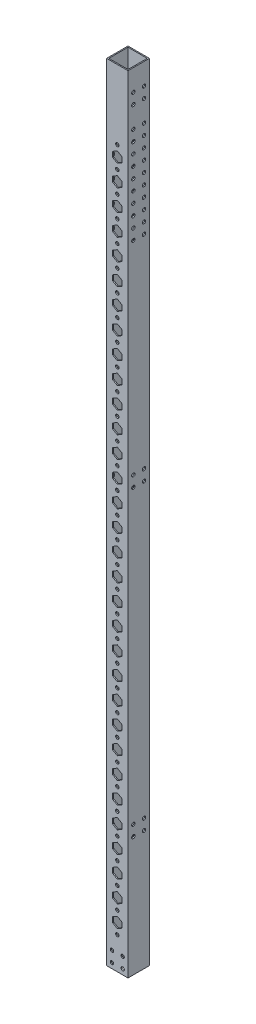
SolidWorks part; units mm, degrees
ref_plane "前视基准面" through (0, 0, 0) normal (0, 0, 1) x (1, 0, 0)
ref_plane "上视基准面" through (0, 0, 0) normal (0, 1, 0) x (1, 0, 0)
ref_plane "右视基准面" through (0, 0, 0) normal (1, 0, 0) x (0, 0, -1)
other "Configuration Table"
sketch "草图1" plane through (0, 0, 0) normal (0, 1, 0) x (1, 0, 0)
  line L1 (-10, -10) -> (10, -10)
  line L2 (-10, -10) -> (-10, 10)
  line L3 (-10, 10) -> (10, 10)
  line L4 (10, -10) -> (10, 10)
  line L5 (-10, -10) -> (10, 10) construction
  line L6 (-10, 10) -> (10, -10) construction
  point P0 (0, 0)
  dimension "D1" = 20
  dimension "D2" = 20
extrude "拉伸-薄壁1" add sketch "草图1" along normal blind 735 thin thin type one direction reverse wall 1
sketch "草图4" plane through (0, 0, 10) normal (0, 0, 1) x (1, 0, 0)
  line L0 (-10, 0) -> (10, 0) construction
  line L1 (0, 30) -> (0, 0) construction
  line L2 (10, 10) -> (-10, 10) construction
  line L3 (10, 735) -> (10, 0) construction
  line L4 (-10, 735) -> (-10, 0) construction
  line L5 (0, 30) -> (0, 50) construction
  line L6 (4.3301, 62.5) -> (0, 65)
  line L7 (0, 45) -> (-4.3301, 42.5)
  line L8 (-4.3301, 42.5) -> (-4.3301, 37.5)
  line L9 (-4.3301, 37.5) -> (0, 35)
  line L10 (0, 35) -> (4.3301, 37.5)
  line L11 (4.3301, 37.5) -> (4.3301, 42.5)
  line L12 (4.3301, 42.5) -> (0, 45)
  line L13 (4.3301, 57.5) -> (4.3301, 62.5)
  line L14 (0, 55) -> (4.3301, 57.5)
  line L15 (-4.3301, 57.5) -> (0, 55)
  line L16 (-4.3301, 62.5) -> (-4.3301, 57.5)
  line L17 (0, 65) -> (-4.3301, 62.5)
  line L18 (4.3301, 82.5) -> (0, 85)
  line L19 (4.3301, 77.5) -> (4.3301, 82.5)
  line L20 (0, 75) -> (4.3301, 77.5)
  line L21 (-4.3301, 77.5) -> (0, 75)
  line L22 (-4.3301, 82.5) -> (-4.3301, 77.5)
  line L23 (0, 85) -> (-4.3301, 82.5)
  line L24 (4.3301, 102.5) -> (0, 105)
  line L25 (4.3301, 97.5) -> (4.3301, 102.5)
  line L26 (0, 95) -> (4.3301, 97.5)
  line L27 (-4.3301, 97.5) -> (0, 95)
  line L28 (-4.3301, 102.5) -> (-4.3301, 97.5)
  line L29 (0, 105) -> (-4.3301, 102.5)
  line L30 (4.3301, 122.5) -> (0, 125)
  line L31 (4.3301, 117.5) -> (4.3301, 122.5)
  line L32 (0, 115) -> (4.3301, 117.5)
  line L33 (-4.3301, 117.5) -> (0, 115)
  line L34 (-4.3301, 122.5) -> (-4.3301, 117.5)
  line L35 (0, 125) -> (-4.3301, 122.5)
  line L36 (4.3301, 142.5) -> (0, 145)
  line L37 (4.3301, 137.5) -> (4.3301, 142.5)
  line L38 (0, 135) -> (4.3301, 137.5)
  line L39 (-4.3301, 137.5) -> (0, 135)
  line L40 (-4.3301, 142.5) -> (-4.3301, 137.5)
  line L41 (0, 145) -> (-4.3301, 142.5)
  line L42 (4.3301, 162.5) -> (0, 165)
  line L43 (4.3301, 157.5) -> (4.3301, 162.5)
  line L44 (0, 155) -> (4.3301, 157.5)
  line L45 (-4.3301, 157.5) -> (0, 155)
  line L46 (-4.3301, 162.5) -> (-4.3301, 157.5)
  line L47 (0, 165) -> (-4.3301, 162.5)
  line L48 (4.3301, 182.5) -> (0, 185)
  line L49 (4.3301, 177.5) -> (4.3301, 182.5)
  line L50 (0, 175) -> (4.3301, 177.5)
  line L51 (-4.3301, 177.5) -> (0, 175)
  line L52 (-4.3301, 182.5) -> (-4.3301, 177.5)
  line L53 (0, 185) -> (-4.3301, 182.5)
  line L54 (4.3301, 202.5) -> (0, 205)
  line L55 (4.3301, 197.5) -> (4.3301, 202.5)
  line L56 (0, 195) -> (4.3301, 197.5)
  line L57 (-4.3301, 197.5) -> (0, 195)
  line L58 (-4.3301, 202.5) -> (-4.3301, 197.5)
  line L59 (0, 205) -> (-4.3301, 202.5)
  line L60 (4.3301, 222.5) -> (0, 225)
  line L61 (4.3301, 217.5) -> (4.3301, 222.5)
  line L62 (0, 215) -> (4.3301, 217.5)
  line L63 (-4.3301, 217.5) -> (0, 215)
  line L64 (-4.3301, 222.5) -> (-4.3301, 217.5)
  line L65 (0, 225) -> (-4.3301, 222.5)
  line L66 (4.3301, 242.5) -> (0, 245)
  line L67 (4.3301, 237.5) -> (4.3301, 242.5)
  line L68 (0, 235) -> (4.3301, 237.5)
  line L69 (-4.3301, 237.5) -> (0, 235)
  line L70 (-4.3301, 242.5) -> (-4.3301, 237.5)
  line L71 (0, 245) -> (-4.3301, 242.5)
  line L72 (4.3301, 262.5) -> (0, 265)
  line L73 (4.3301, 257.5) -> (4.3301, 262.5)
  line L74 (0, 255) -> (4.3301, 257.5)
  line L75 (-4.3301, 257.5) -> (0, 255)
  line L76 (-4.3301, 262.5) -> (-4.3301, 257.5)
  line L77 (0, 265) -> (-4.3301, 262.5)
  line L78 (4.3301, 282.5) -> (0, 285)
  line L79 (4.3301, 277.5) -> (4.3301, 282.5)
  line L80 (0, 275) -> (4.3301, 277.5)
  line L81 (-4.3301, 277.5) -> (0, 275)
  line L82 (-4.3301, 282.5) -> (-4.3301, 277.5)
  line L83 (0, 285) -> (-4.3301, 282.5)
  line L84 (4.3301, 302.5) -> (0, 305)
  line L85 (4.3301, 297.5) -> (4.3301, 302.5)
  line L86 (0, 295) -> (4.3301, 297.5)
  line L87 (-4.3301, 297.5) -> (0, 295)
  line L88 (-4.3301, 302.5) -> (-4.3301, 297.5)
  line L89 (0, 305) -> (-4.3301, 302.5)
  line L90 (4.3301, 322.5) -> (0, 325)
  line L91 (4.3301, 317.5) -> (4.3301, 322.5)
  line L92 (0, 315) -> (4.3301, 317.5)
  line L93 (-4.3301, 317.5) -> (0, 315)
  line L94 (-4.3301, 322.5) -> (-4.3301, 317.5)
  line L95 (0, 325) -> (-4.3301, 322.5)
  line L96 (4.3301, 342.5) -> (0, 345)
  line L97 (4.3301, 337.5) -> (4.3301, 342.5)
  line L98 (0, 335) -> (4.3301, 337.5)
  line L99 (-4.3301, 337.5) -> (0, 335)
  line L100 (-4.3301, 342.5) -> (-4.3301, 337.5)
  line L101 (0, 345) -> (-4.3301, 342.5)
  line L102 (4.3301, 362.5) -> (0, 365)
  line L103 (4.3301, 357.5) -> (4.3301, 362.5)
  line L104 (0, 355) -> (4.3301, 357.5)
  line L105 (-4.3301, 357.5) -> (0, 355)
  line L106 (-4.3301, 362.5) -> (-4.3301, 357.5)
  line L107 (0, 365) -> (-4.3301, 362.5)
  line L108 (4.3301, 382.5) -> (0, 385)
  line L109 (4.3301, 377.5) -> (4.3301, 382.5)
  line L110 (0, 375) -> (4.3301, 377.5)
  line L111 (-4.3301, 377.5) -> (0, 375)
  line L112 (-4.3301, 382.5) -> (-4.3301, 377.5)
  line L113 (0, 385) -> (-4.3301, 382.5)
  line L114 (4.3301, 402.5) -> (0, 405)
  line L115 (4.3301, 397.5) -> (4.3301, 402.5)
  line L116 (0, 395) -> (4.3301, 397.5)
  line L117 (-4.3301, 397.5) -> (0, 395)
  line L118 (-4.3301, 402.5) -> (-4.3301, 397.5)
  line L119 (0, 405) -> (-4.3301, 402.5)
  line L120 (4.3301, 422.5) -> (0, 425)
  line L121 (4.3301, 417.5) -> (4.3301, 422.5)
  line L122 (0, 415) -> (4.3301, 417.5)
  line L123 (-4.3301, 417.5) -> (0, 415)
  line L124 (-4.3301, 422.5) -> (-4.3301, 417.5)
  line L125 (0, 425) -> (-4.3301, 422.5)
  line L126 (4.3301, 442.5) -> (0, 445)
  line L127 (4.3301, 437.5) -> (4.3301, 442.5)
  line L128 (0, 435) -> (4.3301, 437.5)
  line L129 (-4.3301, 437.5) -> (0, 435)
  line L130 (-4.3301, 442.5) -> (-4.3301, 437.5)
  line L131 (0, 445) -> (-4.3301, 442.5)
  line L132 (4.3301, 462.5) -> (0, 465)
  line L133 (4.3301, 457.5) -> (4.3301, 462.5)
  line L134 (0, 455) -> (4.3301, 457.5)
  line L135 (-4.3301, 457.5) -> (0, 455)
  line L136 (-4.3301, 462.5) -> (-4.3301, 457.5)
  line L137 (0, 465) -> (-4.3301, 462.5)
  line L138 (4.3301, 482.5) -> (0, 485)
  line L139 (4.3301, 477.5) -> (4.3301, 482.5)
  line L140 (0, 475) -> (4.3301, 477.5)
  line L141 (-4.3301, 477.5) -> (0, 475)
  line L142 (-4.3301, 482.5) -> (-4.3301, 477.5)
  line L143 (0, 485) -> (-4.3301, 482.5)
  line L144 (4.3301, 502.5) -> (0, 505)
  line L145 (4.3301, 497.5) -> (4.3301, 502.5)
  line L146 (0, 495) -> (4.3301, 497.5)
  line L147 (-4.3301, 497.5) -> (0, 495)
  line L148 (-4.3301, 502.5) -> (-4.3301, 497.5)
  line L149 (0, 505) -> (-4.3301, 502.5)
  line L150 (4.3301, 522.5) -> (0, 525)
  line L151 (4.3301, 517.5) -> (4.3301, 522.5)
  line L152 (0, 515) -> (4.3301, 517.5)
  line L153 (-4.3301, 517.5) -> (0, 515)
  line L154 (-4.3301, 522.5) -> (-4.3301, 517.5)
  line L155 (0, 525) -> (-4.3301, 522.5)
  line L156 (4.3301, 542.5) -> (0, 545)
  line L157 (4.3301, 537.5) -> (4.3301, 542.5)
  line L158 (0, 535) -> (4.3301, 537.5)
  line L159 (-4.3301, 537.5) -> (0, 535)
  line L160 (-4.3301, 542.5) -> (-4.3301, 537.5)
  line L161 (0, 545) -> (-4.3301, 542.5)
  line L162 (4.3301, 562.5) -> (0, 565)
  line L163 (4.3301, 557.5) -> (4.3301, 562.5)
  line L164 (0, 555) -> (4.3301, 557.5)
  line L165 (-4.3301, 557.5) -> (0, 555)
  line L166 (-4.3301, 562.5) -> (-4.3301, 557.5)
  line L167 (0, 565) -> (-4.3301, 562.5)
  line L168 (4.3301, 582.5) -> (0, 585)
  line L169 (4.3301, 577.5) -> (4.3301, 582.5)
  line L170 (0, 575) -> (4.3301, 577.5)
  line L171 (-4.3301, 577.5) -> (0, 575)
  line L172 (-4.3301, 582.5) -> (-4.3301, 577.5)
  line L173 (0, 585) -> (-4.3301, 582.5)
  line L174 (4.3301, 602.5) -> (0, 605)
  line L175 (4.3301, 597.5) -> (4.3301, 602.5)
  line L176 (0, 595) -> (4.3301, 597.5)
  line L177 (-4.3301, 597.5) -> (0, 595)
  line L178 (-4.3301, 602.5) -> (-4.3301, 597.5)
  line L179 (0, 605) -> (-4.3301, 602.5)
  line L180 (4.3301, 622.5) -> (0, 625)
  line L181 (4.3301, 617.5) -> (4.3301, 622.5)
  line L182 (0, 615) -> (4.3301, 617.5)
  line L183 (-4.3301, 617.5) -> (0, 615)
  line L184 (-4.3301, 622.5) -> (-4.3301, 617.5)
  line L185 (0, 625) -> (-4.3301, 622.5)
  line L186 (4.3301, 642.5) -> (0, 645)
  line L187 (4.3301, 637.5) -> (4.3301, 642.5)
  line L188 (0, 635) -> (4.3301, 637.5)
  line L189 (-4.3301, 637.5) -> (0, 635)
  line L190 (-4.3301, 642.5) -> (-4.3301, 637.5)
  line L191 (0, 645) -> (-4.3301, 642.5)
  line L192 (4.3301, 662.5) -> (0, 665)
  line L193 (4.3301, 657.5) -> (4.3301, 662.5)
  line L194 (0, 655) -> (4.3301, 657.5)
  line L195 (-4.3301, 657.5) -> (0, 655)
  line L196 (-4.3301, 662.5) -> (-4.3301, 657.5)
  line L197 (0, 665) -> (-4.3301, 662.5)
  circle A0 centre (0, 30) radius 1.6
  circle A1 centre (0, 50) radius 1.6
  circle A2 centre (0, 70) radius 1.6
  circle A3 centre (0, 90) radius 1.6
  circle A4 centre (0, 110) radius 1.6
  circle A5 centre (0, 130) radius 1.6
  circle A6 centre (0, 150) radius 1.6
  circle A7 centre (0, 170) radius 1.6
  circle A8 centre (0, 190) radius 1.6
  circle A9 centre (0, 210) radius 1.6
  circle A10 centre (0, 230) radius 1.6
  circle A11 centre (0, 250) radius 1.6
  circle A12 centre (0, 270) radius 1.6
  circle A13 centre (0, 290) radius 1.6
  circle A14 centre (0, 310) radius 1.6
  circle A15 centre (0, 330) radius 1.6
  circle A16 centre (0, 350) radius 1.6
  circle A17 centre (0, 370) radius 1.6
  circle A18 centre (0, 390) radius 1.6
  circle A19 centre (0, 410) radius 1.6
  circle A20 centre (0, 430) radius 1.6
  circle A21 centre (0, 450) radius 1.6
  circle A22 centre (0, 470) radius 1.6
  circle A23 centre (0, 490) radius 1.6
  circle A24 centre (0, 510) radius 1.6
  circle A25 centre (0, 530) radius 1.6
  circle A26 centre (0, 550) radius 1.6
  circle A27 centre (0, 570) radius 1.6
  circle A28 centre (0, 590) radius 1.6
  circle A29 centre (0, 610) radius 1.6
  circle A30 centre (0, 630) radius 1.6
  circle A31 centre (0, 650) radius 1.6
  circle A32 centre (0, 670) radius 1.6
  circle A33 centre (5, 5) radius 1.6
  circle A34 centre (-5, 5) radius 1.6
  circle A35 centre (-5, 15) radius 1.6
  circle A36 centre (5, 15) radius 1.6
  circle A37 centre (0, 40) radius 4.3301 construction
  circle A38 centre (0, 60) radius 4.3301 construction
  circle A39 centre (0, 80) radius 4.3301 construction
  circle A40 centre (0, 100) radius 4.3301 construction
  circle A41 centre (0, 120) radius 4.3301 construction
  circle A42 centre (0, 140) radius 4.3301 construction
  circle A43 centre (0, 160) radius 4.3301 construction
  circle A44 centre (0, 180) radius 4.3301 construction
  circle A45 centre (0, 200) radius 4.3301 construction
  circle A46 centre (0, 220) radius 4.3301 construction
  circle A47 centre (0, 240) radius 4.3301 construction
  circle A48 centre (0, 260) radius 4.3301 construction
  circle A49 centre (0, 280) radius 4.3301 construction
  circle A50 centre (0, 300) radius 4.3301 construction
  circle A51 centre (0, 320) radius 4.3301 construction
  circle A52 centre (0, 340) radius 4.3301 construction
  circle A53 centre (0, 360) radius 4.3301 construction
  circle A54 centre (0, 380) radius 4.3301 construction
  circle A55 centre (0, 400) radius 4.3301 construction
  circle A56 centre (0, 420) radius 4.3301 construction
  circle A57 centre (0, 440) radius 4.3301 construction
  circle A58 centre (0, 460) radius 4.3301 construction
  circle A59 centre (0, 480) radius 4.3301 construction
  circle A60 centre (0, 500) radius 4.3301 construction
  circle A61 centre (0, 520) radius 4.3301 construction
  circle A62 centre (0, 540) radius 4.3301 construction
  circle A63 centre (0, 560) radius 4.3301 construction
  circle A64 centre (0, 580) radius 4.3301 construction
  circle A65 centre (0, 600) radius 4.3301 construction
  circle A66 centre (0, 620) radius 4.3301 construction
  circle A67 centre (0, 640) radius 4.3301 construction
  circle A68 centre (0, 660) radius 4.3301 construction
  dimension "D1" = 3.2
  dimension "D6" = 3.2
  dimension "D2" = 30
  dimension "D4" = 20
  dimension "D5" = 10
  dimension "D7" = 5
  dimension "D8" = 5
  dimension "D9" = 5
  dimension "D10" = 15
  dimension "D3" = 33
extrude "切除-拉伸2" cut sketch "草图4" against normal through all
sketch "草图5" plane through (10, 0, 0) normal (1, 0, 0) x (0, 0, -1)
  line L0 (-10, 710) -> (10, 710) construction
  line L1 (-10, 735) -> (-10, 0) construction
  line L2 (10, 735) -> (10, 0) construction
  line L3 (-10, 735) -> (10, 735) construction
  line L4 (0, 735) -> (0, 710) construction
  line L5 (-10, 117) -> (10, 117) construction
  line L6 (-10, 0) -> (10, 0) construction
  line L7 (0, 117) -> (0, 0) construction
  line L8 (-10, 400) -> (10, 400) construction
  line L9 (0, 400) -> (0, 117) construction
  line L10 (-10, 640) -> (10, 640) construction
  circle A0 centre (-5, 715) radius 1.6
  circle A1 centre (5, 715) radius 1.6
  circle A2 centre (5, 705) radius 1.6
  circle A3 centre (-5, 705) radius 1.6
  circle A4 centre (-5, 112) radius 1.6
  circle A5 centre (5, 112) radius 1.6
  circle A6 centre (5, 122) radius 1.6
  circle A7 centre (-5, 122) radius 1.6
  circle A8 centre (-5, 395) radius 1.6
  circle A9 centre (5, 395) radius 1.6
  circle A10 centre (5, 405) radius 1.6
  circle A11 centre (-5, 405) radius 1.6
  circle A12 centre (-5, 645) radius 1.6
  circle A13 centre (5, 645) radius 1.6
  circle A14 centre (5, 635) radius 1.6
  circle A15 centre (-5, 635) radius 1.6
  circle A16 centre (-5, 625) radius 1.6
  circle A17 centre (5, 625) radius 1.6
  circle A18 centre (5, 615) radius 1.6
  circle A19 centre (-5, 615) radius 1.6
  circle A20 centre (-5, 605) radius 1.6
  circle A21 centre (5, 605) radius 1.6
  circle A22 centre (5, 595) radius 1.6
  circle A23 centre (-5, 595) radius 1.6
  circle A24 centre (-5, 685) radius 1.6
  circle A25 centre (5, 685) radius 1.6
  circle A26 centre (5, 675) radius 1.6
  circle A27 centre (-5, 675) radius 1.6
  circle A28 centre (-5, 665) radius 1.6
  circle A29 centre (5, 665) radius 1.6
  circle A30 centre (5, 655) radius 1.6
  circle A31 centre (-5, 655) radius 1.6
  dimension "D2" = 3.2
  dimension "D6" = 3.2
  dimension "D10" = 3.2
  dimension "D14" = 3.2
  dimension "D1" = 25
  dimension "D3" = 5
  dimension "D4" = 5
  dimension "D5" = 117
  dimension "D7" = 5
  dimension "D8" = 5
  dimension "D9" = 400
  dimension "D11" = 5
  dimension "D12" = 5
  dimension "D13" = 95
  dimension "D15" = 5
  dimension "D16" = 5
  dimension "D17" = 20
extrude "切除-拉伸3" cut sketch "草图5" against normal through all
